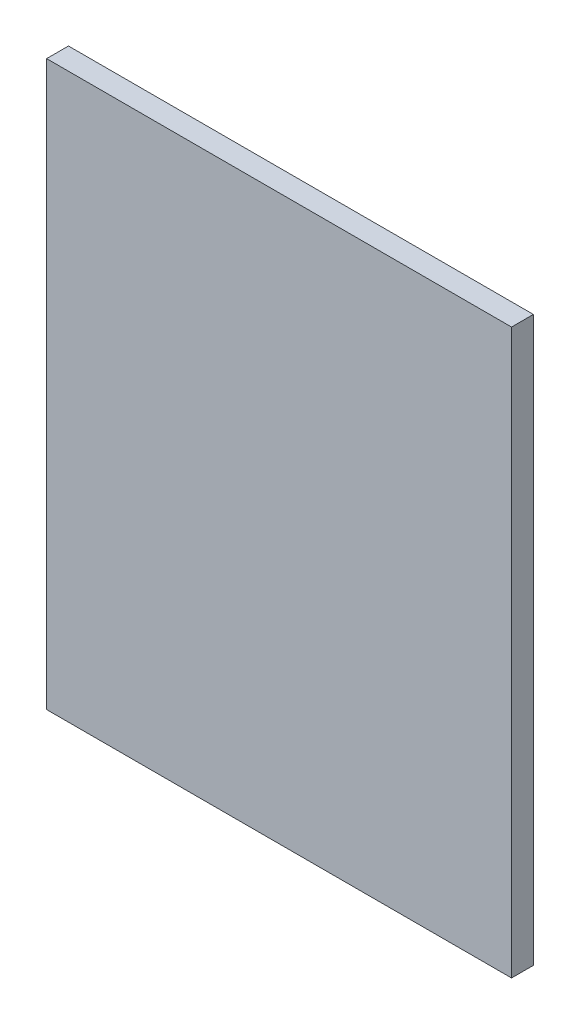
SolidWorks part; units mm, degrees
ref_plane "Front Plane" through (0, 0, 0) normal (0, 0, 1) x (1, 0, 0)
ref_plane "Top Plane" through (0, 0, 0) normal (0, 1, 0) x (1, 0, 0)
ref_plane "Right Plane" through (0, 0, 0) normal (1, 0, 0) x (0, 0, -1)
other "Configuration Table"
sketch "Sketch1" plane through (0, 0, 0) normal (0, 0, 1) x (1, 0, 0)
  line L1 (61.5, 121.5) -> (1338.5, 121.5)
  line L2 (61.5, 121.5) -> (61.5, 1670)
  line L3 (61.5, 1670) -> (1338.5, 1670)
  line L4 (1338.5, 121.5) -> (1338.5, 1670)
extrude "STORE_pu_arka_1" add sketch "Sketch1" against normal blind 60 from offset 758.5 separate body
